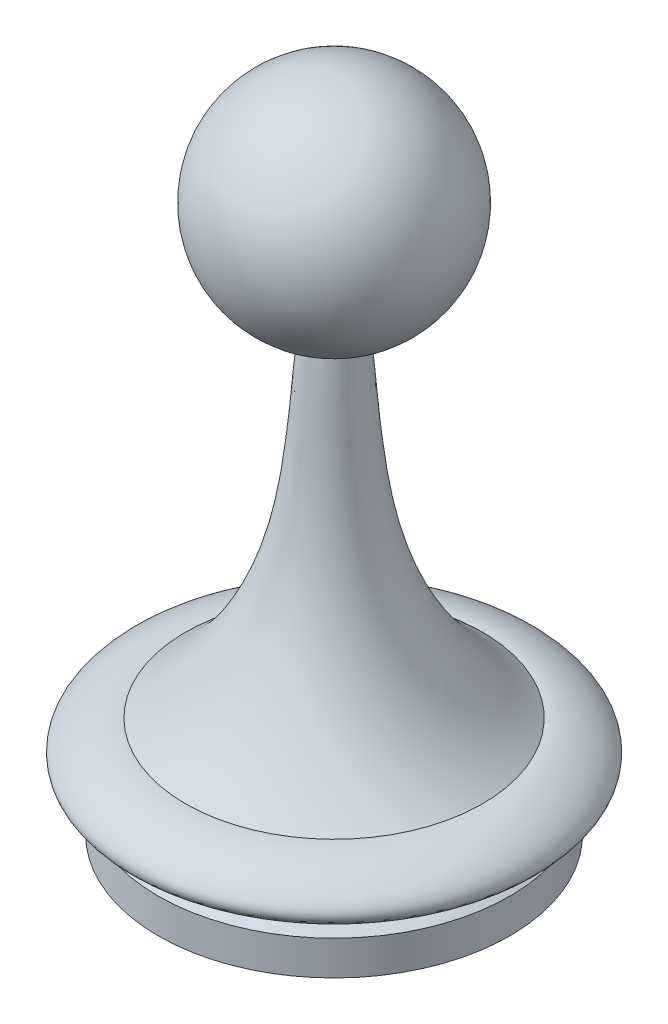
SolidWorks part; units mm, degrees
ref_plane "Front Plane" through (0, 0, 0) normal (0, 0, 1) x (1, 0, 0)
ref_plane "Top Plane" through (0, 0, 0) normal (0, 1, 0) x (1, 0, 0)
ref_plane "Right Plane" through (0, 0, 0) normal (1, 0, 0) x (0, 0, -1)
sketch "Sketch1" plane through (0, 0, 0) normal (0, 0, 1) x (1, 0, 0)
  line L0 (0, 0) -> (0, -1.91)
  line L1 (0, -1.91) -> (0.51, -1.91)
  line L2 (0.51, -1.91) -> (0.51, -1.81)
  line L3 (0.51, -1.81) -> (0.4313, -1.76)
  arc A0 (0.0738, -0.6339) -> (0, 0) centre (0, -0.3212) ccw
  spline S0 degree 3 poles (0.4313, -1.76) (0.7388, -1.7436) (0.5221, -1.6075) (0.4313, -1.617) knots 0 0 0 0 1 1 1 1
  spline S1 degree 3 poles (0.4313, -1.617) (0.2925, -1.515) (0.0978, -1.19) (0.0936, -0.8214) (0.0738, -0.6339) knots 0 0 0 0 0.472391 1 1 1 1
  point P12 (0.51, -1.81)
  point P14 (0.6147, -1.6713)
  point P16 (0.6203, -1.6081)
  point P17 (0.5787, -1.6764)
  point P18 (0.353, -1.5517)
  point P19 (0.51, -1.6111)
  point P20 (0.4313, -1.617)
  point P21 (0.51, -1.6319)
  point P22 (0, 0)
  point P23 (0.2817, -1.4655)
  point P24 (0, 0)
  point P25 (0, 0)
  point P26 (0.151, -1.1982)
  point P27 (0.0738, -0.325)
  point P28 (0.0946, -0.8715)
  point P29 (0.0738, -0.6339)
  point P30 (0, 0.0218)
  point P31 (0, 0)
  dimension "D4" = 0.05
  dimension "D1" = 1.91
  dimension "D2" = 0.51
  dimension "D3" = 0.1
revolve "Revolve1" add sketch "Sketch1" angle 360 about L0
